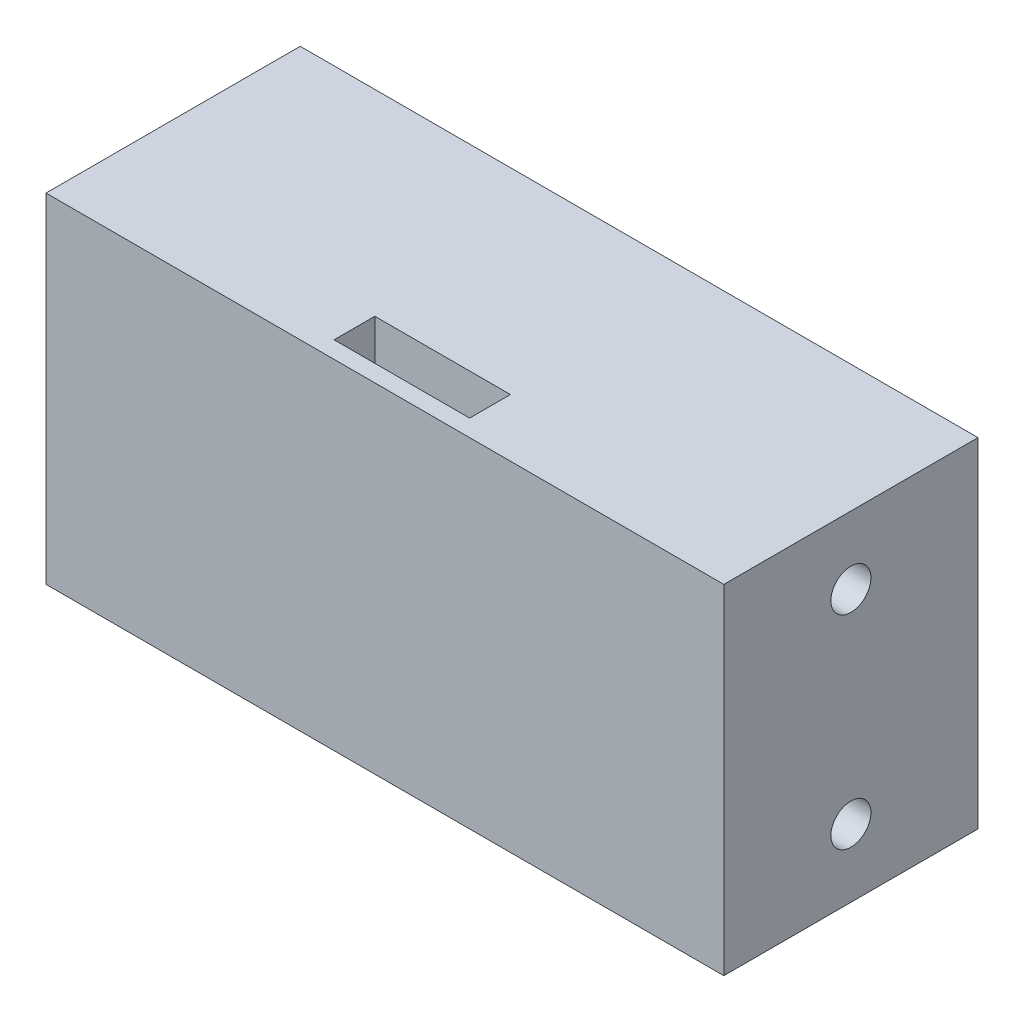
SolidWorks part; units mm, degrees
ref_plane "Front Plane" through (0, 0, 0) normal (0, 0, 1) x (1, 0, 0)
ref_plane "Top Plane" through (0, 0, 0) normal (0, 1, 0) x (1, 0, 0)
ref_plane "Right Plane" through (0, 0, 0) normal (1, 0, 0) x (0, 0, -1)
sketch "Sketch1" plane through (0, 0, 0) normal (0, 0, 1) x (1, 0, 0)
  line L1 (25.4, -12.7) -> (-25.4, -12.7)
  line L2 (25.4, -12.7) -> (25.4, 12.7)
  line L3 (25.4, 12.7) -> (-25.4, 12.7)
  line L4 (-25.4, -12.7) -> (-25.4, 12.7)
  line L5 (25.4, -12.7) -> (-25.4, 12.7) construction
  line L6 (25.4, 12.7) -> (-25.4, -12.7) construction
  point P0 (0, 0)
  dimension "D1" = 50.8
  dimension "D2" = 25.4
extrude "Boss-Extrude1" add sketch "Sketch1" along normal blind 19.05
sketch "Sketch4" plane through (0, 12.7, 0) normal (0, 1, 0) x (1, 0, 0)
  line L0 (25.4, -19.05) -> (25.4, 0) construction
  line L3 (25.4, -19.05) -> (-25.4, -19.05) construction
  line L4 (0, -19.05) -> (0, -1.5875) construction
  line L9 (-5.08, -3.175) -> (-5.08, -14.7254) construction
  line L11 (5.08, -3.175) -> (5.08, -14.7254) construction
  line L12 (5.08, -14.7254) -> (-5.08, -14.7254) construction
  line L15 (5.08, -14.7254) -> (-5.08, -14.7254)
  line L16 (5.08, -14.7254) -> (5.08, -17.78)
  line L17 (5.08, -17.78) -> (-5.08, -17.78)
  line L18 (-5.08, -14.7254) -> (-5.08, -17.78)
  dimension "D1" = 10.16
  dimension "D2" = 20.32
  dimension "D3" = 1.27
extrude "Cut-Extrude2" cut sketch "Sketch4" against normal blind 19.05
sketch "Sketch5" plane through (0, 0, 0) normal (0, 0, -1) x (-1, 0, 0)
  line L0 (0, 12.7) -> (0, -12.7) construction
  line L1 (-25.4, 12.7) -> (25.4, 12.7) construction
  line L2 (25.4, -12.7) -> (-25.4, -12.7) construction
  line L3 (25.4, -6.35) -> (-25.4, -6.35) construction
  line L4 (25.4, 12.7) -> (25.4, -12.7) construction
  line L5 (-25.4, -12.7) -> (-25.4, 12.7) construction
  line L7 (5.08, -6.35) -> (-5.08, -6.35)
  line L8 (5.08, -6.35) -> (5.08, -9.525)
  line L9 (5.08, -9.525) -> (-5.08, -9.525)
  line L10 (-5.08, -6.35) -> (-5.08, -9.525)
  dimension "D1" = 19.05
  dimension "D2" = 3.175
  dimension "D3" = 10.16
  dimension "D4" = 20.32
extrude "Cut-Extrude3" cut sketch "Sketch5" against normal blind 17.78
sketch "Sketch6" plane through (-25.4, 0, 0) normal (-1, 0, 0) x (0, 0, 1)
  line L0 (9.525, -12.7) -> (9.525, 12.7) construction
  line L1 (19.05, -12.7) -> (0, -12.7) construction
  line L2 (19.05, 12.7) -> (0, 12.7) construction
  circle A0 centre (9.525, -7.62) radius 1.5
  circle A1 centre (9.525, 7.62) radius 1.5
  dimension "D1" = 3
  dimension "D2" = 3
  dimension "D3" = 5.08
  dimension "D4" = 5.08
extrude "Cut-Extrude4" cut sketch "Sketch6" against normal blind 10.16
sketch "Sketch7" plane through (25.4, 0, 0) normal (1, 0, 0) x (0, 0, -1)
  line L0 (-9.525, 12.7) -> (-9.525, -12.7) construction
  line L1 (-19.05, 12.7) -> (0, 12.7) construction
  line L2 (-19.05, -12.7) -> (0, -12.7) construction
  circle A0 centre (-9.525, 7.62) radius 1.5
  circle A1 centre (-9.525, -7.62) radius 1.5
  dimension "D1" = 3
  dimension "D2" = 3
  dimension "D3" = 5.08
  dimension "D4" = 5.08
extrude "Cut-Extrude5" cut sketch "Sketch7" against normal blind 10.16
sketch "Sketch8" plane through (0, 0, 0) normal (0, 0, -1) x (-1, 0, 0)
  line L0 (25.4, 0) -> (-25.4, 0) construction
  line L1 (25.4, 12.7) -> (25.4, -12.7) construction
  line L2 (-25.4, -12.7) -> (-25.4, 12.7) construction
  line L3 (22.225, -12.7) -> (22.225, 12.7) construction
  line L4 (25.4, -12.7) -> (-25.4, -12.7) construction
  line L5 (-25.4, 12.7) -> (25.4, 12.7) construction
  line L6 (-22.225, -12.7) -> (-22.225, 12.7) construction
  circle A0 centre (22.225, 0) radius 1.5
  circle A1 centre (-22.225, 0) radius 1.5
  dimension "D3" = 3
  dimension "D4" = 3
  dimension "D1" = 3.175
  dimension "D2" = 3.175
extrude "Cut-Extrude6" cut sketch "Sketch8" against normal blind 10.16
